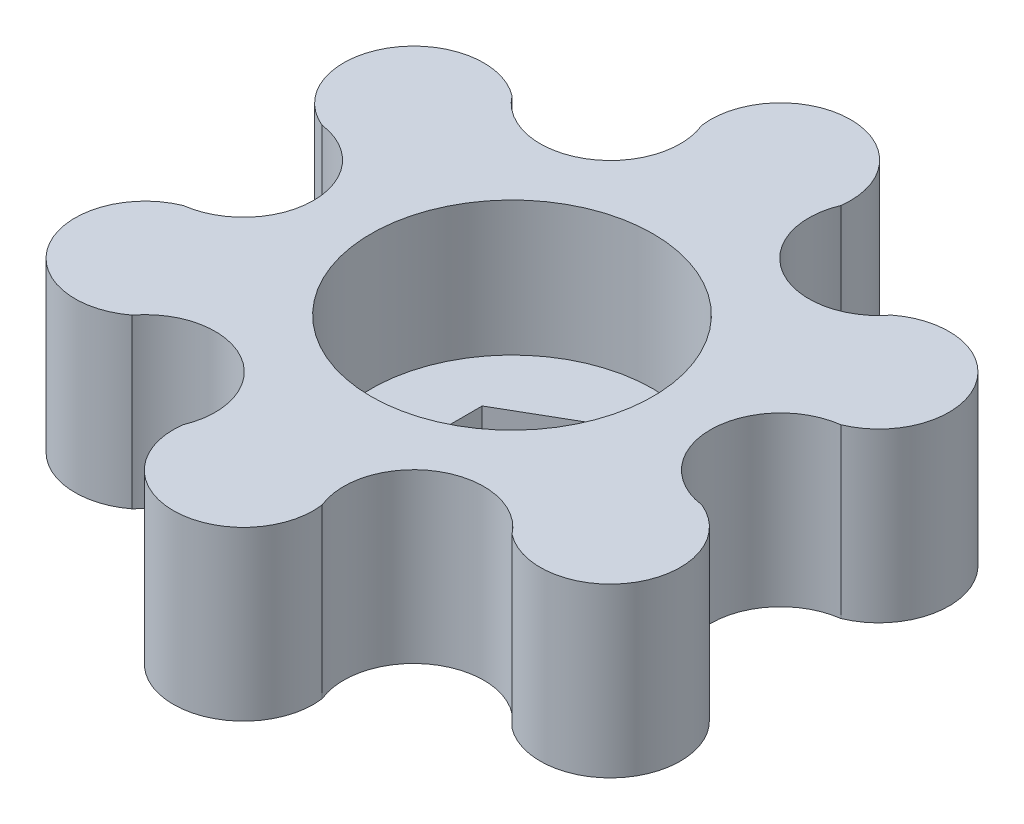
SolidWorks part; units mm, degrees
ref_plane "Front Plane" through (0, 0, 0) normal (0, 0, 1) x (1, 0, 0)
ref_plane "Top Plane" through (0, 0, 0) normal (0, 1, 0) x (1, 0, 0)
ref_plane "Right Plane" through (0, 0, 0) normal (1, 0, 0) x (0, 0, -1)
sketch "Sketch1" plane through (0, 0, 0) normal (0, 1, 0) x (1, 0, 0)
  line L0 (0, 8.5891) -> (0, 0) construction
  circle A0 centre (0, 0) radius 4.2
  arc A4 (2.0706, 7.7274) -> (-2.0706, 7.7274) centre (0, 8) ccw
  circle A5 centre (0, 0) radius 8 construction
  arc A6 (2.0706, 7.7274) -> (5.6569, 5.6569) centre (4, 6.9282) ccw
  arc A7 (7.7274, 2.0706) -> (5.6569, 5.6569) centre (6.9282, 4) ccw
  arc A8 (7.7274, 2.0706) -> (7.7274, -2.0706) centre (8, 0) ccw
  arc A9 (5.6569, -5.6569) -> (7.7274, -2.0706) centre (6.9282, -4) ccw
  arc A10 (5.6569, -5.6569) -> (2.0706, -7.7274) centre (4, -6.9282) ccw
  arc A11 (-2.0706, -7.7274) -> (2.0706, -7.7274) centre (0, -8) ccw
  arc A12 (-2.0706, -7.7274) -> (-5.6569, -5.6569) centre (-4, -6.9282) ccw
  arc A13 (-7.7274, -2.0706) -> (-5.6569, -5.6569) centre (-6.9282, -4) ccw
  arc A14 (-7.7274, -2.0706) -> (-7.7274, 2.0706) centre (-8, 0) ccw
  arc A15 (-5.6569, 5.6569) -> (-7.7274, 2.0706) centre (-6.9282, 4) ccw
  arc A16 (-5.6569, 5.6569) -> (-2.0706, 7.7274) centre (-4, 6.9282) ccw
  point P9 (-3.1828, 9.48)
  point P11 (-11.6859, -17.4247)
  point P15 (0, 0)
  point P16 (0, 0)
  point P18 (0, 0)
  point P23 (0, 0)
  point P38 (0, 0)
  dimension "D1" = 8.4
  dimension "D2" = 16
  dimension "D3" = 6
extrude "Boss-Extrude1" add sketch "Sketch1" along normal blind 5
sketch "Sketch2" plane through (0, 0, 0) normal (0, -1, 0) x (1, 0, 0)
  line L1 (0, 2.4249) -> (-2.1, 1.2124)
  line L2 (-2.1, 1.2124) -> (-2.1, -1.2124)
  line L3 (-2.1, -1.2124) -> (0, -2.4249)
  line L4 (0, -2.4249) -> (2.1, -1.2124)
  line L5 (2.1, -1.2124) -> (2.1, 1.2124)
  line L6 (2.1, 1.2124) -> (0, 2.4249)
  circle A0 centre (0, 0) radius 4.2 construction
  circle A1 centre (0, 0) radius 4.2
  circle A2 centre (0, 0) radius 2.1 construction
  dimension "D1" = 4.2
extrude "Boss-Extrude2" add sketch "Sketch2" against normal blind 1
